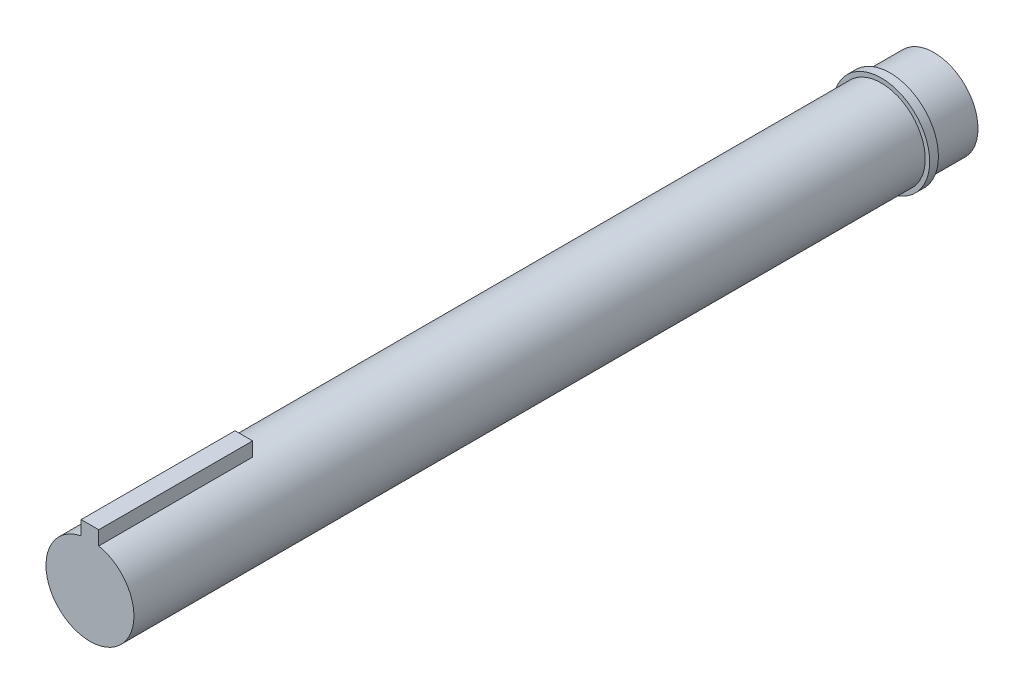
SolidWorks part; units mm, degrees
ref_plane "Front Plane" through (0, 0, 0) normal (0, 0, 1) x (1, 0, 0)
ref_plane "Top Plane" through (0, 0, 0) normal (0, 1, 0) x (1, 0, 0)
ref_plane "Right Plane" through (0, 0, 0) normal (1, 0, 0) x (0, 0, -1)
sketch "Sketch1" plane through (0, 0, 0) normal (0, 0, 1) x (1, 0, 0)
  circle A0 centre (0, 0) radius 12.7
  dimension "D1" = 25.4
extrude "Boss-Extrude1" add sketch "Sketch1" along normal blind 12.7 contours A0
sketch "Sketch2" plane through (0, 0, 12.7) normal (0, 0, 1) x (1, 0, 0)
  circle A0 centre (0, 0) radius 13.97
  dimension "D1" = 27.94
extrude "Boss-Extrude2" add sketch "Sketch2" along normal blind 2.54
sketch "Sketch3" plane through (0, 0, 15.24) normal (0, 0, 1) x (1, 0, 0)
  circle A0 centre (0, 0) radius 12.7
  dimension "D1" = 25.4
extrude "Boss-Extrude3" add sketch "Sketch3" along normal blind 228.6
sketch "Sketch4" plane through (0, 0, 243.84) normal (0, 0, 1) x (1, 0, 0)
  line L0 (0, 0) -> (0, 16.51) construction
  line L1 (-2.54, 16.51) -> (2.54, 16.51)
  line L2 (2.54, 16.51) -> (2.54, 12.4434)
  line L3 (-2.54, 16.51) -> (-2.54, 12.4434)
  circle A0 centre (0, 0) radius 12.7 construction
  circle A1 centre (0, 0) radius 12.7 construction
  arc A2 (2.54, 12.4434) -> (-2.54, 12.4434) centre (0, 0) ccw
  dimension "D1" = 16.51
  dimension "D2" = 2.54
extrude "Boss-Extrude4" add sketch "Sketch4" against normal blind 44.45 contours L1 L2 A2 L3
